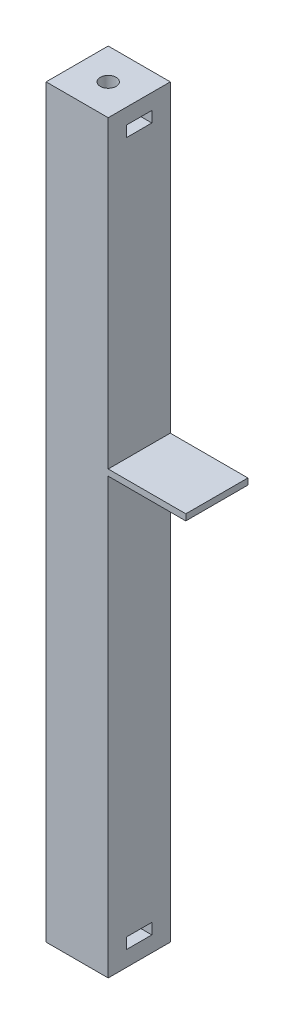
SolidWorks part; units mm, degrees
ref_plane "Plan de face" through (0, 0, 0) normal (0, 0, 1) x (1, 0, 0)
ref_plane "Plan de dessus" through (0, 0, 0) normal (0, 1, 0) x (1, 0, 0)
ref_plane "Plan de droite" through (0, 0, 0) normal (1, 0, 0) x (0, 0, -1)
sketch "Esquisse1" plane through (0, 0, 0) normal (0, 1, 0) x (1, 0, 0)
  line L1 (-10, 10) -> (10, 10)
  line L2 (-10, 10) -> (-10, -10)
  line L3 (-10, -10) -> (10, -10)
  line L4 (10, 10) -> (10, -10)
  line L5 (-10, 10) -> (10, -10) construction
  line L6 (-10, -10) -> (10, 10) construction
  point P0 (0, 0)
  dimension "D1" = 20
  dimension "D2" = 20
extrude "Boss.-Extru.2" add sketch "Esquisse1" along normal blind 240
sketch "Esquisse5" plane through (10, 0, 0) normal (1, 0, 0) x (0, 0, -1)
  line L0 (10, 120) -> (-10, 120) construction
  line L1 (-10, 235) -> (10, 235) construction
  line L2 (-10, 231.5) -> (10, 231.5) construction
  line L3 (0, 240) -> (0, 197.7299) construction
  line L4 (4.05, 235) -> (-4.05, 235)
  line L5 (4.05, 231.5) -> (-4.05, 231.5)
  line L6 (-4.05, 235) -> (-4.05, 231.5)
  line L7 (4.05, 235) -> (4.05, 231.5)
  line L11 (-10, 240) -> (-10, 0)
  line L12 (-10, 0) -> (10, 0)
  line L13 (10, 0) -> (10, 240)
  line L14 (10, 240) -> (-10, 240)
  line L19 (-10, 240) -> (-10, 0)
  line L20 (-10, 0) -> (10, 0)
  line L21 (10, 0) -> (10, 240)
  line L22 (10, 240) -> (-10, 240)
  line L24 (4.05, 5) -> (-4.05, 5)
  line L25 (-4.05, 5) -> (-4.05, 8.5)
  line L26 (4.05, 8.5) -> (-4.05, 8.5)
  line L27 (4.05, 5) -> (4.05, 8.5)
  point P20 (0, 235)
  point P23 (0, 231.5)
  dimension "D2" = 3.5
  dimension "D3" = 8.1
  dimension "D4" = 5
  dimension "D5" = 5
  dimension "D1" = 0
extrude "Enlèv. mat.-Extru.2" cut sketch "Esquisse5" against normal blind 10 contours L7 L5 L6 L4 | L24 L25 L26 L27
sketch "Esquisse6" plane through (0, 240, 0) normal (0, 1, 0) x (1, 0, 0)
  line L4 (10, -10) -> (10, 10)
  line L5 (10, 10) -> (-10, 10)
  line L6 (-10, 10) -> (-10, -10)
  line L7 (-10, -10) -> (10, -10)
  line L8 (10, -10) -> (10, 10)
  line L9 (10, 10) -> (-10, 10)
  line L10 (-10, 10) -> (-10, -10)
  line L11 (-10, -10) -> (10, -10)
  circle A0 centre (0, 0) radius 2.55
  dimension "D2" = 5.1
  dimension "D1" = 0
extrude "Enlèv. mat.-Extru.3" cut sketch "Esquisse6" against normal blind 25 contours A0
sketch "Esquisse7" plane through (0, 231.5, 0) normal (0, 1, 0) x (1, 0, 0)
  line L0 (0, 0) -> (10, 0) construction
  line L1 (2.3383, -4.05) -> (4.6765, 0)
  line L2 (4.6765, 0) -> (2.3383, 4.05)
  line L3 (2.3383, 4.05) -> (-2.3383, 4.05)
  line L4 (10, -4.05) -> (10, 4.05)
  line L5 (10, 4.05) -> (0, 4.05)
  line L6 (0, 4.05) -> (0, 2.55)
  line L7 (0, -4.05) -> (10, -4.05)
  line L8 (10, -4.05) -> (10, 4.05)
  line L9 (10, 4.05) -> (0, 4.05)
  line L10 (0, 4.05) -> (0, 2.55)
  line L11 (0, -4.05) -> (10, -4.05)
  line L12 (-2.3383, 4.05) -> (-4.6765, 0)
  line L13 (-4.6765, 0) -> (-2.3383, -4.05)
  line L14 (-2.3383, -4.05) -> (2.3383, -4.05)
  line L20 (0, -2.55) -> (0, -4.05)
  line L21 (0, -2.55) -> (0, -4.05)
  circle A0 centre (0, 0) radius 2.55 construction
  circle A1 centre (0, 0) radius 2.55
  circle A2 centre (0, 0) radius 4.05 construction
  arc A4 (0, -2.55) -> (0, 2.55) centre (0, 0) ccw
  arc A5 (0, -2.55) -> (0, 2.55) centre (0, 0) ccw
  line M16 (0, 4.05) -> (0, 2.55)
  line M24 (0, -2.55) -> (0, -4.05)
  dimension "D2" = 8.1
  dimension "D1" = 0
extrude "Enlèv. mat.-Extru.5" cut sketch "Esquisse7" along normal blind 3.5 contours A1 L3 L12 L13 L14 M16 M24
sketch "Esquisse9" plane through (0, 0, 0) normal (0, -1, 0) x (1, 0, 0)
  line L4 (10, -10) -> (10, 10)
  line L5 (10, 10) -> (-10, 10)
  line L6 (-10, 10) -> (-10, -10)
  line L7 (-10, -10) -> (10, -10)
  line L8 (10, -10) -> (10, 10)
  line L9 (10, 10) -> (-10, 10)
  line L10 (-10, 10) -> (-10, -10)
  line L11 (-10, -10) -> (10, -10)
  circle A0 centre (0, 0) radius 2.55
  dimension "D2" = 5.1
  dimension "D1" = 0
extrude "Enlèv. mat.-Extru.6" cut sketch "Esquisse9" against normal blind 25 contours A0
sketch "Esquisse10" plane through (10, 0, 0) normal (1, 0, 0) x (0, 0, -1)
  line L0 (-10, 142) -> (10, 142)
  line L1 (-10, 140) -> (10, 140)
  line L4 (-10, 0) -> (10, 0)
  line L5 (10, 0) -> (10, 240)
  line L6 (10, 240) -> (-10, 240)
  line L7 (-10, 240) -> (-10, 0)
  line L8 (-10, 0) -> (10, 0)
  line L9 (10, 0) -> (10, 240)
  line L10 (10, 240) -> (-10, 240)
  line L11 (-10, 240) -> (-10, 0)
  line M16 (10, 0) -> (10, 240)
  line M18 (-10, 240) -> (-10, 0)
  dimension "D2" = 2
  dimension "D3" = 140
  dimension "D1" = 0
extrude "Boss.-Extru.5" add sketch "Esquisse10" along normal blind 25 contours L1 L0 M18 M16
